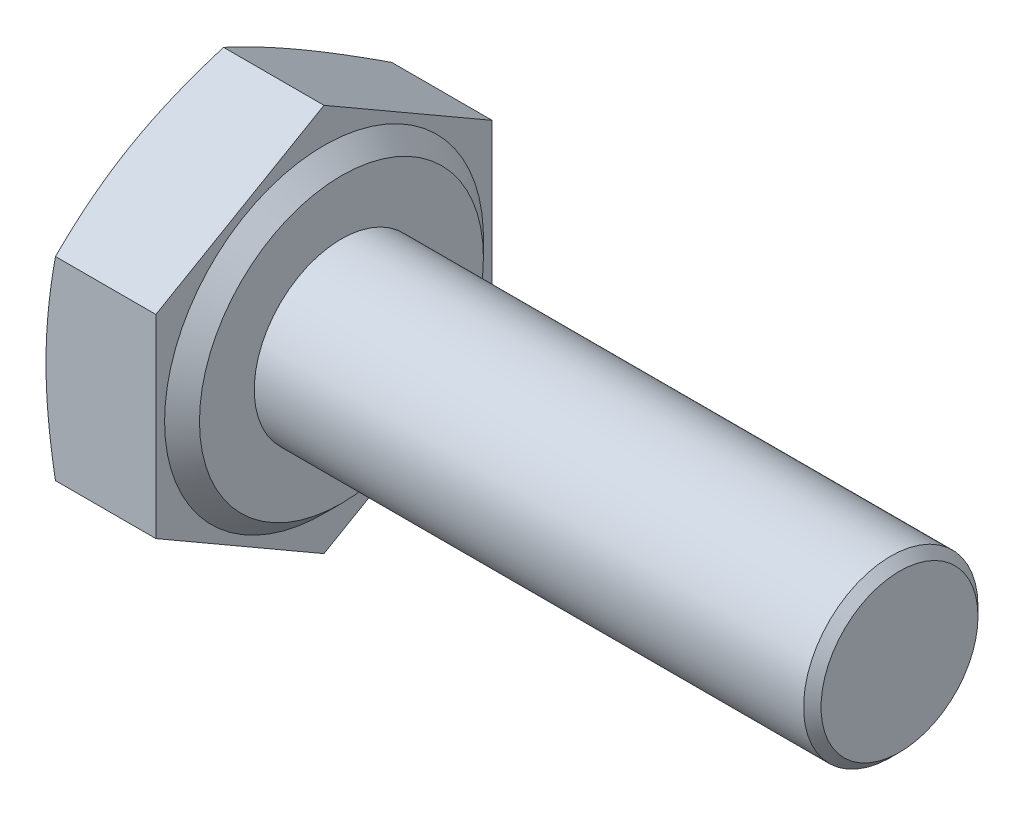
SolidWorks part; units mm, degrees
ref_plane "Front" through (0, 0, 0) normal (0, 0, 1) x (1, 0, 0)
ref_plane "Top" through (0, 0, 0) normal (0, 1, 0) x (1, 0, 0)
ref_plane "Right" through (0, 0, 0) normal (1, 0, 0) x (0, 0, -1)
sketch "Sketch2" plane through (0, 0, 0) normal (1, 0, 0) x (0, 0, -1)
  line L1 (2.41, -1.3914) -> (2.41, 1.3914)
  line L2 (2.41, 1.3914) -> (0, 2.7828)
  line L3 (0, 2.7828) -> (-2.41, 1.3914)
  line L4 (-2.41, 1.3914) -> (-2.41, -1.3914)
  line L5 (-2.41, -1.3914) -> (0, -2.7828)
  line L6 (0, -2.7828) -> (2.41, -1.3914)
  circle A0 centre (0, 0) radius 2.41 construction
  dimension "s" = 4.82
extrude "BaseHead" add sketch "Sketch2" along normal blind 1.825
sketch "Sketch3" plane through (0, 0, 0) normal (0, 0, 1) x (1, 0, 0)
  line L0 (1.825, 2.7828) -> (1.825, 2.035)
  line L2 (1.825, 2.035) -> (1.575, 2.285)
  line L3 (1.575, 2.285) -> (1.575, 2.7828)
  line L5 (1.575, 2.7828) -> (1.825, 2.7828)
  line L6 (-0.9571, 0) -> (7.6478, 0) construction
  line L7 (1.825, 2.7828) -> (0, 2.7828) construction
  dimension "D1" = 45
  dimension "c" = 0.25
  dimension "Dw" = 4.07
revolve "BearingFace" cut sketch "Sketch3" angle 360 about L6
sketch "Sketch4" plane through (0, 0, 0) normal (0, 0, 1) x (1, 0, 0)
  line L0 (-0.4935, 0) -> (3.5626, 0) construction
  line L2 (0, 2.7828) -> (0.1357, 2.7828)
  line L4 (0.1357, 2.7828) -> (0, 2.41)
  line L6 (0, 2.41) -> (0, 2.7828)
  line L7 (1.575, 2.7828) -> (0, 2.7828) construction
  dimension "D1" = 20
  dimension "D2" = 4.82
revolve "HeadChamfer" cut sketch "Sketch4" angle 360 about L0
sketch "Sketch5" plane through (1.825, 0, 0) normal (1, 0, 0) x (0, 0, -1)
  circle A0 centre (0, 0) radius 1.25
  dimension "d" = 2.5
extrude "BaseBody" add sketch "Sketch5" along normal blind 8
cosmetic thread "ThreadCosmetic1" [suppressed] parameters "D2"=2.013
chamfer "Chamfer1" distance 0.125 angle 45 1 edges at (9.825, 0, -1.25)
fillet "HeadFillet" [suppressed] radius 0.1
sketch "Sketch6" plane through (0, 0, 0) normal (0, 0, 1) x (1, 0, 0)
  line L0 (1.825, 1.4935) -> (2.0685, 1.4935)
  line L1 (2.0685, 1.4935) -> (2.0685, 1.25)
  line L2 (2.0685, 1.25) -> (1.9467, 1.0391)
  line L3 (1.9467, 1.0391) -> (1.825, 1.25)
  line L4 (1.825, 1.25) -> (1.825, 1.4935)
  line L5 (9.7, 1.25) -> (1.825, 1.25) construction
  line L6 (1.825, -2.035) -> (1.825, 2.035) construction
  dimension "D1" = 0.2435
revolve "Cut-Revolve10" [suppressed] cut sketch "Sketch6" angle 360 about axis through (-0.9571, 0, 0) along (1, 0, 0)
pattern_linear "LPattern10" [suppressed] count 27
equation "\"D2@Sketch4\" = \"s@Sketch2\""
equation "\"D1@Chamfer1\" = 0.05 * \"d@Sketch5\""
equation "\"D1@Sketch6\" =  ( \"d@Sketch5\" - \"D2@ThreadCosmetic1\" )  / 2"
equation "\"pitch@LPattern10\" = \"D1@Sketch6\" * 1.2"
equation "\"D1@LPattern10\" = \"l@BaseBody\" / \"pitch@LPattern10\""
